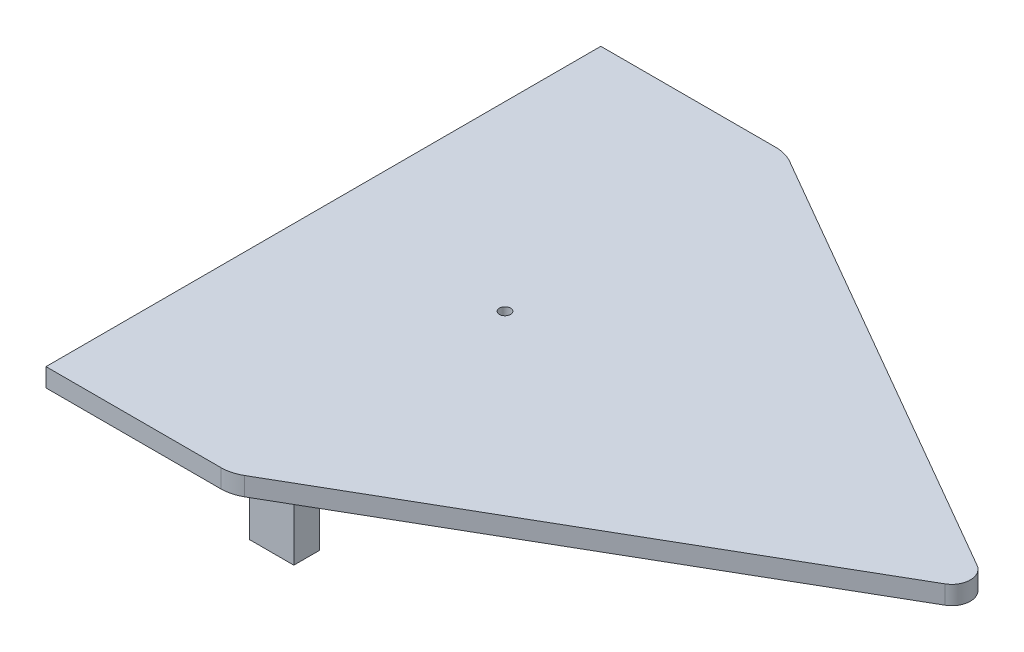
SolidWorks part; units mm, degrees
ref_plane "Alzado" through (0, 0, 0) normal (0, 0, 1) x (1, 0, 0)
ref_plane "Planta" through (0, 0, 0) normal (0, 1, 0) x (1, 0, 0)
ref_plane "Vista lateral" through (0, 0, 0) normal (1, 0, 0) x (0, 0, -1)
sketch "Sketch1" plane through (0, 0, 0) normal (0, 1, 0) x (1, 0, 0)
  line L1 (75.0555, 0) -> (-54.8483, 75)
  line L3 (-54.8483, -75) -> (75.0555, 0)
  line L4 (-54.8483, 75) -> (-104.8483, 75)
  line L6 (-54.8483, -75) -> (-104.8483, -75)
  line L7 (-104.8483, 75) -> (-104.8483, -75)
  line L9 (-37.5278, 70.8049) -> (-37.5278, -59.1951) [skipped]
  circle A0 centre (0, 0) radius 37.5278 construction
  dimension "D3" = 75.0555
  dimension "D1" = 150
  dimension "D2" = 50
  dimension "D4" = 50
  dimension "D5" = 150
extrude "Boss-Extrude1" add sketch "Sketch1" along normal blind 5 contours L4 L7 L6 L3 L1
fillet "Fillet1" radius 5 1 edges at (75.0555, 2.5, 0)
fillet "Fillet2" radius 10 1 edges at (-54.8483, 2.5, -75)
fillet "Fillet3" radius 10 1 edges at (-54.8483, 2.5, 75)
sketch "Sketch3" plane through (0, 5, 0) normal (0, 1, 0) x (1, 0, 0)
  line L0 (-57.5278, 75) -> (-104.8483, 75) construction
  line L15 (-100.8483, -71) -> (-57.5278, -71)
  line L16 (-54.5278, -70.1962) -> (65.5555, -0.866)
  line L17 (65.5555, 0.866) -> (-54.5278, 70.1962)
  line L18 (-57.5278, 71) -> (-100.8483, 71)
  line L19 (-100.8483, 71) -> (-100.8483, -71)
  line L20 (-100.8483, -71) -> (-57.5278, -71)
  line L21 (-54.5278, -70.1962) -> (65.5555, -0.866)
  line L22 (65.5555, 0.866) -> (-54.5278, 70.1962)
  line L23 (-57.5278, 71) -> (-100.8483, 71)
  line L24 (-100.8483, 71) -> (-100.8483, -71)
  circle A0 centre (-55.7545, 0) radius 1.5
  arc A9 (-57.5278, -71) -> (-54.5278, -70.1962) centre (-57.5278, -65) ccw
  arc A10 (65.5555, -0.866) -> (65.5555, 0.866) centre (65.0555, 0) ccw
  arc A11 (-54.5278, 70.1962) -> (-57.5278, 71) centre (-57.5278, 65) ccw
  arc A12 (-57.5278, -71) -> (-54.5278, -70.1962) centre (-57.5278, -65) ccw
  arc A13 (65.5555, -0.866) -> (65.5555, 0.866) centre (65.0555, 0) ccw
  arc A14 (-54.5278, 70.1962) -> (-57.5278, 71) centre (-57.5278, 65) ccw
  dimension "D2" = 3
  dimension "D3" = 45.0938
  dimension "D4" = 75
  dimension "D1" = 4
extrude "Cut-Extrude1" cut sketch "Sketch3" against normal blind 3.5 contours A0
ref_plane "Plane1" through (-85.3483, 8, 9.4935) normal (-1, 0, 0) x (0, 0, 1)
sketch "Sketch5" plane through (0, 0, 0) normal (0, -1, 0) x (1, 0, 0)
  line L0 (-57.5278, -75) -> (-104.8483, -75) construction
  line L1 (-89.8483, -35) -> (-77.8483, -35)
  line L2 (-89.8483, -35) -> (-89.8483, -28)
  line L3 (-89.8483, -28) -> (-77.8483, -28)
  line L4 (-77.8483, -35) -> (-77.8483, -28)
  line L5 (-104.8483, -75) -> (-104.8483, 75) construction
  dimension "D1" = 40
  dimension "D2" = 7
  dimension "D3" = 15
  dimension "D4" = 12
extrude "Boss-Extrude2" add sketch "Sketch5" along normal blind 48
fillet "Fillet4" radius 10 4 edges at (-83.8483, 0, -28) (-77.8483, 0, -31.5) (-89.8483, 0, -31.5) (-83.8483, 0, -35)
sketch "Sketch6" plane through (0, -48, 0) normal (0, -1, 0) x (1, 0, 0)
  line L1 (-85.8483, -27) -> (-81.8483, -27)
  line L2 (-85.8483, -27) -> (-85.8483, -31)
  line L3 (-85.8483, -31) -> (-81.8483, -31)
  line L4 (-81.8483, -27) -> (-81.8483, -31)
  dimension "D1" = 4
  dimension "D2" = 4
extrude "Cut-Extrude2" cut sketch "Sketch6" against normal blind 30
mirror "Mirror1" about plane through (0, 0, 0) normal (0, 0, 1) of "Cut-Extrude2", "Boss-Extrude2", "Fillet4"
